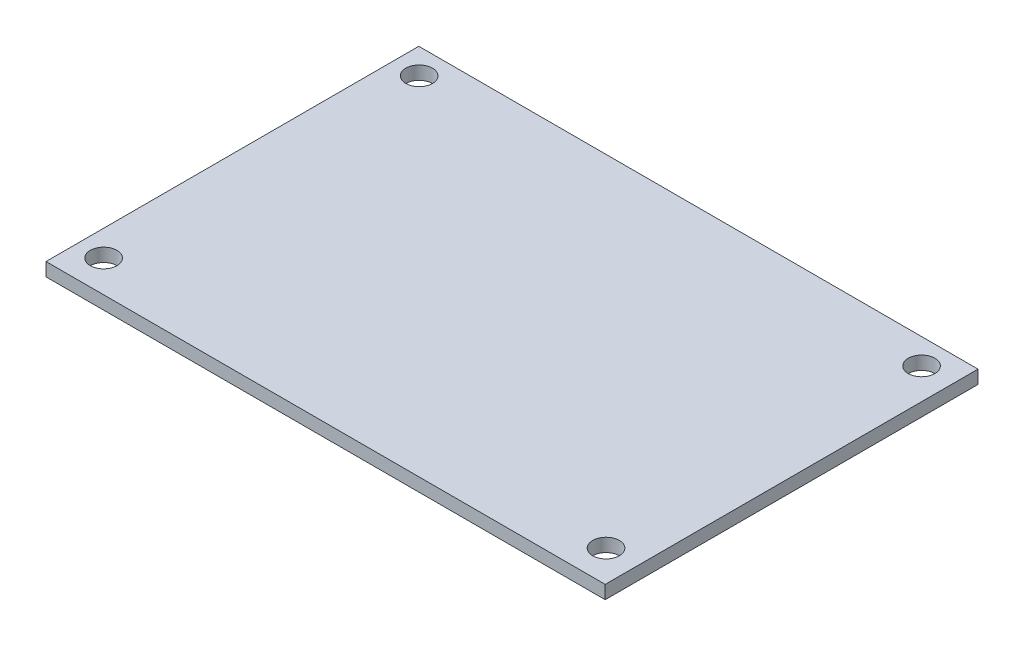
SolidWorks part; units mm, degrees
ref_plane "Front Plane" through (0, 0, 0) normal (0, 0, 1) x (1, 0, 0)
ref_plane "Top Plane" through (0, 0, 0) normal (0, 1, 0) x (1, 0, 0)
ref_plane "Right Plane" through (0, 0, 0) normal (1, 0, 0) x (0, 0, -1)
sketch "Sketch1" plane through (0, 0, 0) normal (0, 1, 0) x (1, 0, 0)
  line L1 (-31.5, 21) -> (31.5, 21)
  line L2 (-31.5, 21) -> (-31.5, -21)
  line L3 (-31.5, -21) -> (31.5, -21)
  line L4 (31.5, 21) -> (31.5, -21)
  line L5 (-31.5, 21) -> (31.5, -21) construction
  line L6 (-31.5, -21) -> (31.5, 21) construction
  point P0 (0, 0)
extrude "Boss-Extrude1" add sketch "Sketch1" along normal blind 1.5
sketch "Sketch2" plane through (0, 1.5, 0) normal (0, 1, 0) x (1, 0, 0)
  circle A0 centre (-28.5976, 18.1358) radius 1.5
  circle A1 centre (28.0072, 18.1358) radius 1.5
  circle A2 centre (28.0072, -17.4143) radius 1.5
  circle A3 centre (-28.5976, -17.4143) radius 1.5
extrude "Cut-Extrude1" cut sketch "Sketch2" against normal through all
